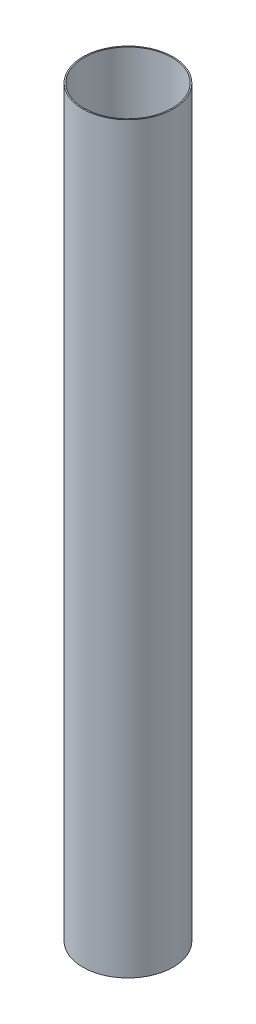
SolidWorks part; units mm, degrees
material "A-Glass Fiber"
ref_plane "Front Plane" through (0, 0, 0) normal (0, 0, 1) x (1, 0, 0)
ref_plane "Top Plane" through (0, 0, 0) normal (0, 1, 0) x (1, 0, 0)
ref_plane "Right Plane" through (0, 0, 0) normal (1, 0, 0) x (0, 0, -1)
sketch "Sketch1" plane through (0, 0, 0) normal (0, 1, 0) x (1, 0, 0)
  circle A0 centre (0, 0) radius 76
  circle A1 centre (0, 0) radius 74
  dimension "D1" = 152
  dimension "D2" = 148
extrude "Boss-Extrude2" add sketch "Sketch1" along normal blind 1250
